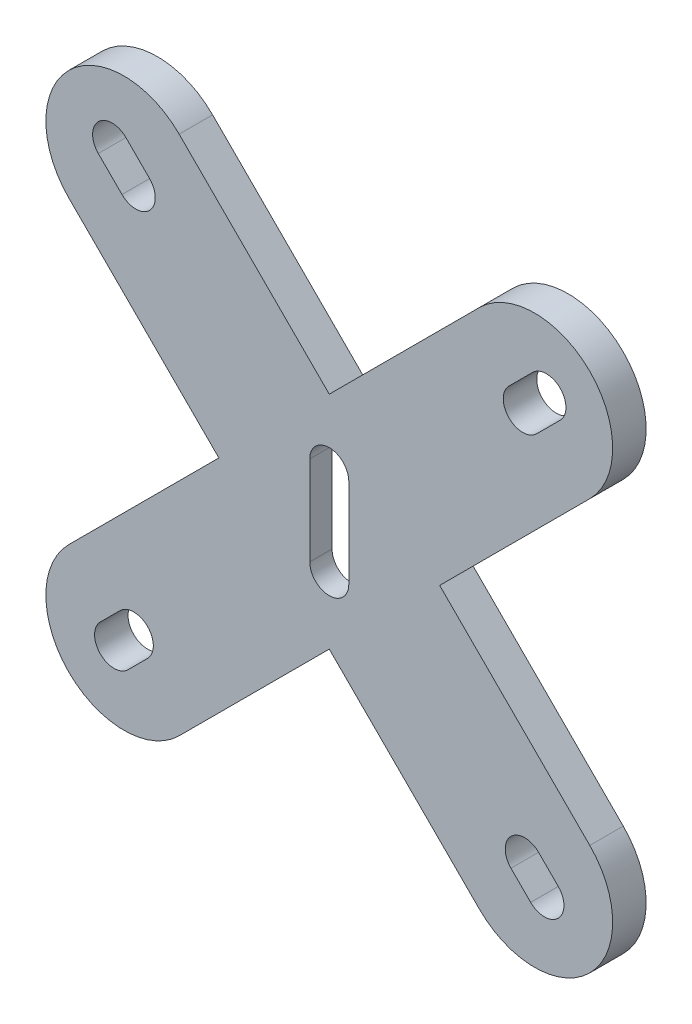
SolidWorks part; units mm, degrees
ref_plane "Front Plane" through (0, 0, 0) normal (0, 0, 1) x (1, 0, 0)
ref_plane "Top Plane" through (0, 0, 0) normal (0, 1, 0) x (1, 0, 0)
ref_plane "Right Plane" through (0, 0, 0) normal (1, 0, 0) x (0, 0, -1)
sketch "Sketch1" plane through (0, 0, 0) normal (0, 0, 1) x (1, 0, 0)
  line L0 (-5.0165, 48.0165) -> (48.0165, -5.0165)
  line L1 (0, 0) -> (43, 0) construction
  line L2 (0, 0) -> (0, 43) construction
  line L3 (0, 43) -> (43, 43) construction
  line L4 (43, 0) -> (43, 43) construction
  circle A0 centre (21.5, 21.5) radius 37.5
  dimension "D3" = 75
  dimension "D1" = 43
  dimension "D2" = 43
extrude "Boss-Extrude1" add sketch "Sketch1" along normal blind 3 contours L0 A0 | L0 A0
sketch "Sketch2" plane through (0, 0, 0) normal (0, 0, -1) x (-1, 0, 0)
  line L0 (-38.8518, 38.8518) -> (-40.9732, 40.9732) construction
  line L1 (-40.0893, 37.6144) -> (-42.2106, 39.7357)
  line L2 (-37.6144, 40.0893) -> (-39.7357, 42.2106)
  line L3 (-4.1482, 38.8518) -> (-2.0268, 40.9732) construction
  line L4 (5.0165, 48.0165) -> (-48.0165, -5.0165) construction
  line L5 (-5.3856, 40.0893) -> (-3.2643, 42.2106)
  line L6 (-2.9107, 37.6144) -> (-0.7894, 39.7357)
  line L7 (-40.7964, 2.2036) -> (-39.0286, 3.9714) construction
  line L8 (-42.0338, 3.4411) -> (-40.2661, 5.2088)
  line L9 (-39.5589, 0.9662) -> (-37.7912, 2.7339)
  line L10 (-2.2036, 2.2036) -> (-3.9714, 3.9714) construction
  line L11 (-3.4411, 0.9662) -> (-5.2088, 2.7339)
  line L12 (-0.9662, 3.4411) -> (-2.7339, 5.2088)
  arc A4 (-40.0893, 37.6144) -> (-37.6144, 40.0893) centre (-38.8518, 38.8518) ccw
  arc A5 (-39.7357, 42.2106) -> (-42.2106, 39.7357) centre (-40.9732, 40.9732) ccw
  arc A6 (-5.3856, 40.0893) -> (-2.9107, 37.6144) centre (-4.1482, 38.8518) ccw
  arc A7 (-0.7894, 39.7357) -> (-3.2643, 42.2106) centre (-2.0268, 40.9732) ccw
  arc A8 (-42.0338, 3.4411) -> (-39.5589, 0.9662) centre (-40.7964, 2.2036) ccw
  arc A9 (-37.7912, 2.7339) -> (-40.2661, 5.2088) centre (-39.0286, 3.9714) ccw
  arc A10 (-3.4411, 0.9662) -> (-0.9662, 3.4411) centre (-2.2036, 2.2036) ccw
  arc A11 (-2.7339, 5.2088) -> (-5.2088, 2.7339) centre (-3.9714, 3.9714) ccw
  point P14 (-39.9125, 39.9125)
  point P21 (-3.0875, 39.9125)
  point P26 (-39.9125, 3.0875)
  point P31 (-3.0875, 3.0875)
  dimension "D2" = 3.5
  dimension "D3" = 3
  dimension "D4" = 2.5
  dimension "D7" = 3.5
  dimension "D8" = 3.5
  dimension "D9" = 2.5
  dimension "D5" = 3.5
  dimension "D6" = 3
extrude "Cut-Extrude1" cut sketch "Sketch2" against normal blind 10
sketch "Sketch3" plane through (0, 0, 0) normal (0, 0, -1) x (-1, 0, 0)
  line L1 (5.0165, 48.0165) -> (-48.0165, -5.0165) construction
  line L2 (-34.9628, 44.8622) -> (-21.5, 31.3995)
  line L3 (-44.8622, 34.9628) -> (-31.3995, 21.5)
  line L5 (1.8622, 34.9628) -> (-11.6005, 21.5)
  line L6 (-8.0372, 44.8622) -> (-21.5, 31.3995)
  line L7 (-21.5, 11.6005) -> (-34.9628, -1.8622)
  line L8 (-11.6005, 21.5) -> (1.8622, 8.0372)
  line L9 (-31.3995, 21.5) -> (-44.8622, 8.0372)
  line L12 (-21.5, 11.6005) -> (-8.0372, -1.8622)
  arc A0 (-34.9628, 44.8622) -> (-44.8622, 34.9628) centre (-39.9125, 39.9125) ccw
  arc A1 (-8.0372, -1.8622) -> (1.8622, 8.0372) centre (-3.0875, 3.0875) ccw
  arc A2 (1.8622, 34.9628) -> (-8.0372, 44.8622) centre (-3.0875, 39.9125) ccw
  arc A3 (-44.8622, 8.0372) -> (-34.9628, -1.8622) centre (-39.9125, 3.0875) ccw
  point P5 (-21.5, 21.5)
  point P12 (-21.5, 21.5)
  dimension "D1" = 14
  dimension "D2" = 14
extrude "Cut-Extrude2" cut sketch "Sketch3" against normal blind 10 flip side to cut
sketch "Sketch5" plane through (0, 0, 0) normal (0, 0, -1) x (-1, 0, 0)
  line L0 (0, 21.5) -> (-43, 21.5) construction
  circle A0 centre (-21.5, 21.5) radius 7.5
  dimension "D1" = 15
extrude "Cut-Extrude3" cut sketch "Sketch5" against normal blind 1
sketch "Sketch6" plane through (0, 0, 1) normal (0, 0, -1) x (-1, 0, 0)
  line L0 (-21.5, 17.5) -> (-21.5, 25.5) construction
  line L1 (0, 21.5) -> (-43, 21.5) construction
  line L2 (-21.5, 0) -> (-21.5, 43) construction
  line L3 (-23.25, 17.5) -> (-23.25, 25.5)
  line L4 (-19.75, 17.5) -> (-19.75, 25.5)
  arc A0 (-23.25, 17.5) -> (-19.75, 17.5) centre (-21.5, 17.5) ccw
  arc A1 (-19.75, 25.5) -> (-23.25, 25.5) centre (-21.5, 25.5) ccw
  point P6 (-21.5, 21.5)
  dimension "D1" = 8
  dimension "D2" = 3.5
extrude "Cut-Extrude4" cut sketch "Sketch6" against normal blind 2
